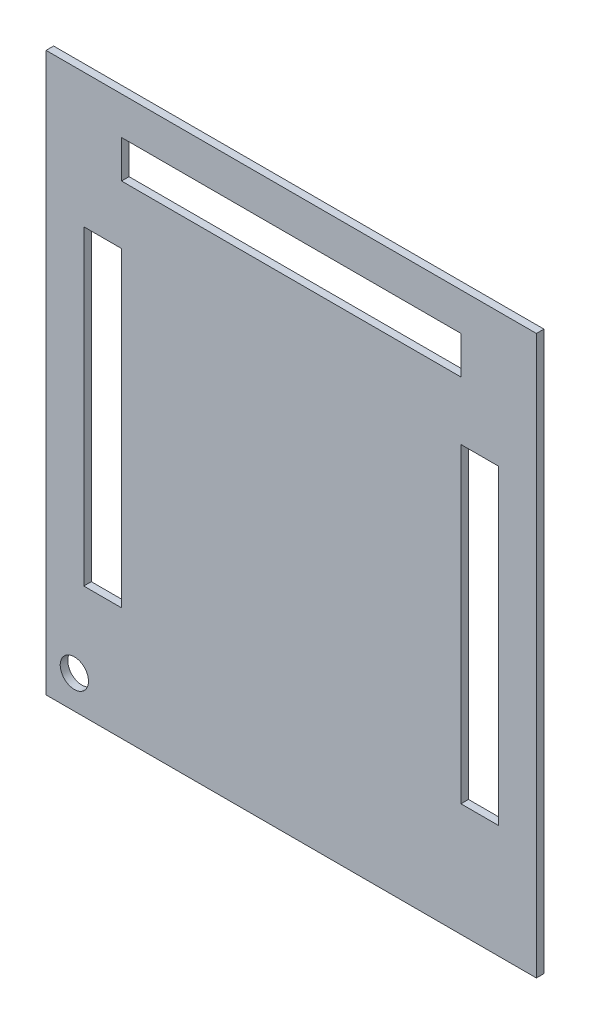
SolidWorks part; units mm, degrees
ref_plane "Alzado" through (0, 0, 0) normal (0, 0, 1) x (1, 0, 0)
ref_plane "Planta" through (0, 0, 0) normal (0, 1, 0) x (1, 0, 0)
ref_plane "Vista lateral" through (0, 0, 0) normal (1, 0, 0) x (0, 0, -1)
sketch "Croquis1" plane through (0, 0, 0) normal (0, 0, 1) x (1, 0, 0)
  line L1 (0, 0) -> (260, 0)
  line L2 (0, 0) -> (0, 296)
  line L3 (0, 296) -> (260, 296)
  line L4 (260, 0) -> (260, 296)
extrude "Saliente-Extruir1" add sketch "Croquis1" along normal blind 4
sketch "Croquis2" plane through (0, 0, 4) normal (0, 0, 1) x (1, 0, 0)
  line L0 (130, 296) -> (130, 0) construction
  line L1 (260, 296) -> (0, 296) construction
  line L2 (0, 0) -> (260, 0) construction
  line L3 (260, 0) -> (240, 0) construction
  line L4 (240, 0) -> (240, 60) construction
  line L5 (20, 225) -> (40, 225)
  line L6 (240, 60) -> (220, 60)
  line L7 (240, 60) -> (240, 225)
  line L8 (240, 225) -> (220, 225)
  line L9 (220, 60) -> (220, 225)
  line L10 (20, 60) -> (40, 60)
  line L11 (20, 60) -> (20, 225)
  line L12 (40, 60) -> (40, 225)
  line L13 (260, 296) -> (220, 296) construction
  line L14 (220, 296) -> (220, 276) construction
  line L15 (0, 0) -> (0, 10) construction
  line L16 (220, 276) -> (40, 276)
  line L17 (220, 276) -> (220, 256)
  line L18 (220, 256) -> (40, 256)
  line L19 (40, 276) -> (40, 256)
  line L20 (0, 296) -> (0, 0) construction
  line L21 (0, 10) -> (15, 10) construction
  line L22 (15, 10) -> (15, 17.5) construction
  circle A1 centre (15, 17.5) radius 7.5
extrude "Cortar-Extruir1" cut sketch "Croquis2" against normal blind 4
